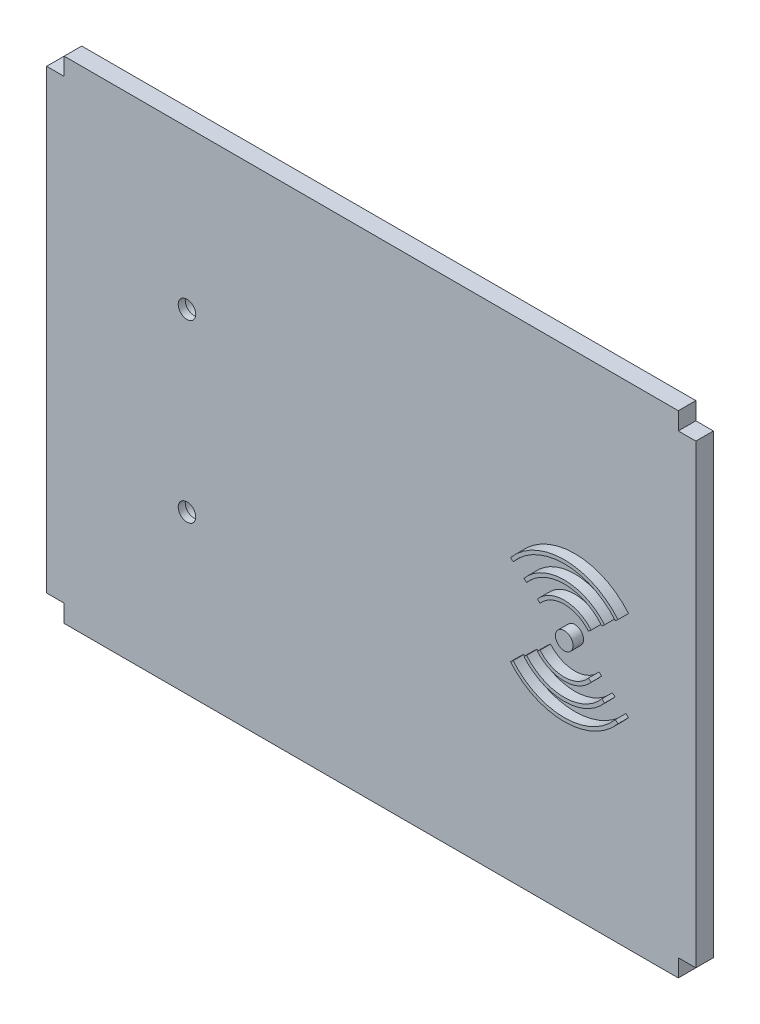
SolidWorks part; units mm, degrees
ref_plane "Front Plane" through (0, 0, 0) normal (0, 0, 1) x (1, 0, 0)
ref_plane "Top Plane" through (0, 0, 0) normal (0, 1, 0) x (1, 0, 0)
ref_plane "Right Plane" through (0, 0, 0) normal (1, 0, 0) x (0, 0, -1)
sketch "Sketch1" plane through (0, 0, 0) normal (0, 0, 1) x (1, 0, 0)
  line L0 (-87.5, 70) -> (-87.5, 65)
  line L1 (-87.5, -70) -> (87.5, -70)
  line L2 (-92.5, -65) -> (-92.5, 65)
  line L3 (-87.5, 70) -> (87.5, 70)
  line L4 (92.5, -65) -> (92.5, 65)
  line L5 (-92.5, -70) -> (92.5, 70) construction
  line L6 (-92.5, 70) -> (92.5, -70) construction
  line L7 (-87.5, 65) -> (-92.5, 65)
  line L8 (87.5, 70) -> (87.5, 65)
  line L9 (87.5, 65) -> (92.5, 65)
  line L10 (87.5, -70) -> (87.5, -65)
  line L11 (87.5, -65) -> (92.5, -65)
  line L12 (-92.5, -65) -> (-87.5, -65)
  line L13 (-87.5, -65) -> (-87.5, -70)
  line L14 (0, 0) -> (0, -13.6132) construction
  line L15 (0, 0) -> (-14.5702, 0) construction
  point P0 (0, 0)
  dimension "D1" = 185
  dimension "D2" = 140
  dimension "D3" = 5
  dimension "D4" = 5
  dimension "D5" = 5
  dimension "D6" = 5
  dimension "D7" = 5
  dimension "D8" = 5
extrude "Boss-Extrude1" add sketch "Sketch1" along normal blind 5
sketch "Sketch2" plane through (0, 0, 5) normal (0, 0, 1) x (1, 0, 0)
  line L0 (0, 0) -> (-103.1434, 0) construction
  line L1 (-92.5, 65) -> (-92.5, -65) construction
  circle A0 centre (-52.5, -25) radius 2.5
  circle A1 centre (-52.5, 25) radius 2.5
  dimension "D3" = 5
  dimension "D4" = 40
  dimension "D1" = 25
  dimension "D2" = 25
extrude "Cut-Extrude1" cut sketch "Sketch2" against normal blind 5
sketch "Sketch3" plane through (0, 0, 0) normal (0, 0, -1) x (-1, 0, 0)
  circle A0 centre (52.5, 25) radius 3
  circle A1 centre (52.5, -25) radius 3
  dimension "D1" = 6
  dimension "D2" = 6
extrude "Cut-Extrude2" cut sketch "Sketch3" against normal blind 3
sketch "Sketch4" plane through (0, 0, 5) normal (0, 0, 1) x (1, 0, 0)
  line L0 (0, 0) -> (81.2255, 0) construction
  line L1 (51.1056, -5.7851) -> (50.3396, -6.4279)
  line L2 (68.7246, -8.999) -> (69.4907, -9.6418)
  line L4 (47.2754, -8.999) -> (46.5093, -9.6418)
  line L5 (43.4452, 12.213) -> (42.6791, 12.8558)
  line L6 (47.2754, 8.999) -> (46.5093, 9.6418)
  line L7 (51.1056, 5.7851) -> (50.3396, 6.4279)
  line L8 (43.4452, -12.213) -> (42.6791, -12.8558)
  line L9 (64.8944, -5.7851) -> (65.6604, -6.4279)
  line L10 (72.5548, -12.213) -> (73.3209, -12.8558)
  line L11 (72.5548, 12.213) -> (73.3209, 12.8558)
  line L12 (68.7246, 8.999) -> (69.4907, 9.6418)
  line L13 (64.8944, 5.7851) -> (65.6604, 6.4279)
  circle A0 centre (58, 0) radius 2.5
  arc A1 (51.1056, -5.7851) -> (64.8944, -5.7851) centre (58, 0) ccw
  arc A2 (47.2754, -8.999) -> (68.7246, -8.999) centre (58, 0) ccw
  arc A3 (43.4452, -12.213) -> (72.5548, -12.213) centre (58, 0) ccw
  arc A4 (50.3396, -6.4279) -> (65.6604, -6.4279) centre (58, 0) ccw
  arc A5 (46.5093, -9.6418) -> (69.4907, -9.6418) centre (58, 0) ccw
  arc A6 (42.6791, -12.8558) -> (73.3209, -12.8558) centre (58, 0) ccw
  arc A7 (73.3209, 12.8558) -> (42.6791, 12.8558) centre (58, 0) ccw
  arc A8 (72.5548, 12.213) -> (43.4452, 12.213) centre (58, 0) ccw
  arc A9 (69.4907, 9.6418) -> (46.5093, 9.6418) centre (58, 0) ccw
  arc A10 (68.7246, 8.999) -> (47.2754, 8.999) centre (58, 0) ccw
  arc A11 (65.6604, 6.4279) -> (50.3396, 6.4279) centre (58, 0) ccw
  arc A12 (64.8944, 5.7851) -> (51.1056, 5.7851) centre (58, 0) ccw
  dimension "D1" = 5
  dimension "D2" = 18
  dimension "D3" = 20
  dimension "D5" = 30
  dimension "D6" = 28
  dimension "D7" = 40
  dimension "D8" = 38
  dimension "D4" = 58
  dimension "D9" = 40
  dimension "D10" = 40
  dimension "D11" = 40
  dimension "D12" = 40
extrude "Boss-Extrude2" add sketch "Sketch4" along normal blind 3
